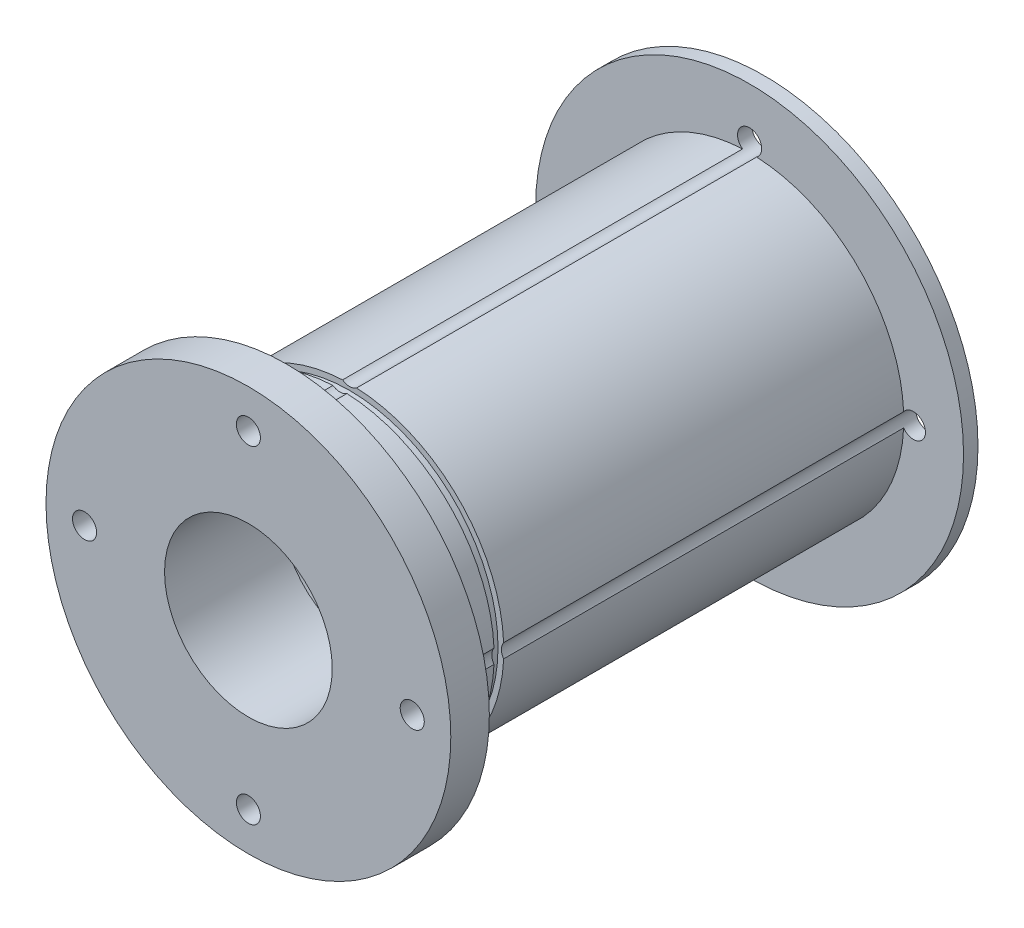
SolidWorks part; units mm, degrees
ref_plane "Спереди" through (0, 0, 0) normal (0, 0, 1) x (1, 0, 0)
ref_plane "Сверху" through (0, 0, 0) normal (0, 1, 0) x (1, 0, 0)
ref_plane "Справа" through (0, 0, 0) normal (1, 0, 0) x (0, 0, -1)
sketch "Эскиз1" plane through (0, 0, 0) normal (0, 0, 1) x (1, 0, 0)
  circle A0 centre (0, 0) radius 16
  circle A1 centre (0, 0) radius 8.7
extrude "Hollow_hub" add sketch "Эскиз1" along normal blind 48 from offset 20
sketch "Эскиз2" plane through (0, 0, 0) normal (0, 0, 1) x (1, 0, 0)
  circle A0 centre (0, 0) radius 22.2
  circle A1 centre (0, 0) radius 13
extrude "Rear_stack_flange" add sketch "Эскиз2" along normal blind 1.5 from offset 21.5
sketch "Эскиз3" plane through (0, 0, 0) normal (0, 0, 1) x (1, 0, 0)
  circle A0 centre (0, 0) radius 21
  circle A1 centre (0, 0) radius 8.7
extrude "Sun_mount_flange" add sketch "Эскиз3" along normal blind 4 from offset 28
sketch "Эскиз4" plane through (0, 0, 0) normal (0, 0, 1) x (1, 0, 0)
  circle A0 centre (0, 0) radius 13
extrude "Rear_rotor_bearing_seat" cut sketch "Эскиз4" along normal blind 5 from offset 20
sketch "Эскиз5" plane through (0, 0, 0) normal (0, 0, 1) x (1, 0, 0)
  circle A0 centre (0, 0) radius 13
extrude "Front_rotor_bearing_seat" cut sketch "Эскиз5" along normal blind 5 from offset 15
sketch "Эскиз6" plane through (0, 0, 0) normal (0, 0, 1) x (1, 0, 0)
  circle A0 centre (0, 0) radius 17
  circle A1 centre (0, 0) radius 15.4
extrude "Circlip_groove" cut sketch "Эскиз6" along normal blind 1 from offset 21.5
sketch "Эскиз7" plane through (0, 0, 0) normal (0, 0, 1) x (1, 0, 0)
  circle A0 centre (17, 0) radius 1.25
  circle A1 centre (0, 17) radius 1.25
  circle A2 centre (-17, 0) radius 1.25
  circle A3 centre (0, -17) radius 1.25
extrude "Through_holes" cut sketch "Эскиз7" against normal mid plane 200
